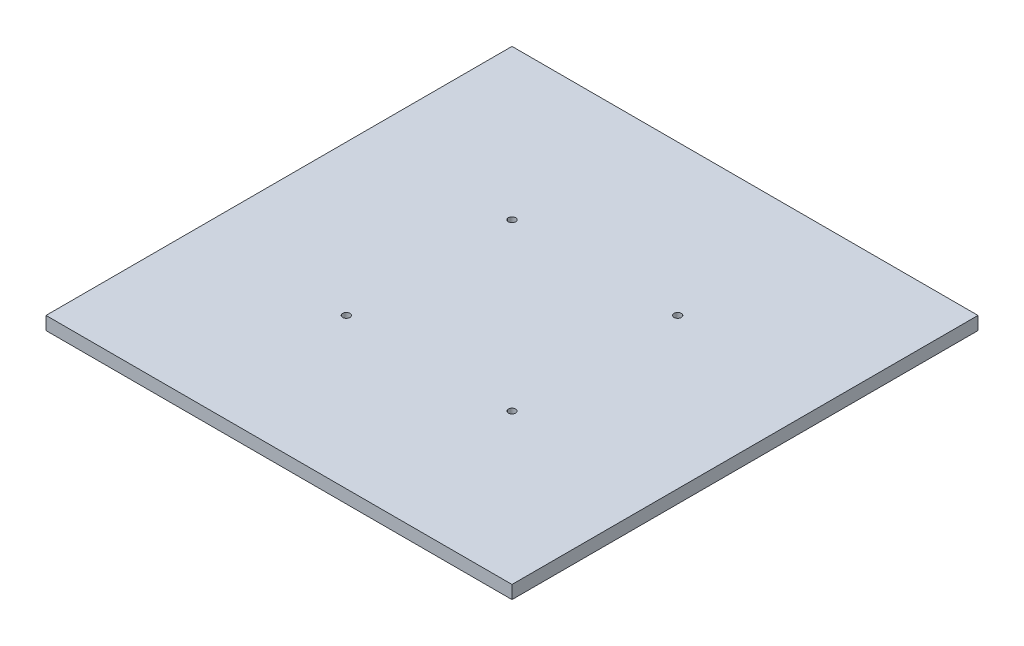
SolidWorks part; units mm, degrees
ref_plane "Front Plane" through (0, 0, 0) normal (0, 0, 1) x (1, 0, 0)
ref_plane "Top Plane" through (0, 0, 0) normal (0, 1, 0) x (1, 0, 0)
ref_plane "Right Plane" through (0, 0, 0) normal (1, 0, 0) x (0, 0, -1)
sketch "Esboço1" plane through (0, 0, 0) normal (0, 1, 0) x (1, 0, 0)
  line L1 (-225, -225) -> (225, -225)
  line L2 (-225, -225) -> (-225, 225)
  line L3 (-225, 225) -> (225, 225)
  line L4 (225, -225) -> (225, 225)
  line L5 (-225, -225) -> (225, 225) construction
  line L6 (-225, 225) -> (225, -225) construction
  point P0 (0, 0)
  dimension "D1" = 450
  dimension "D2" = 450
extrude "Ressalto-extrusão1" add sketch "Esboço1" along normal blind 12.7
sketch "Esboço2" plane through (0, 12.7, 0) normal (0, 1, 0) x (1, 0, 0)
  line L1 (-80, -80) -> (80, -80) construction
  line L2 (-80, -80) -> (-80, 80) construction
  line L3 (-80, 80) -> (80, 80) construction
  line L4 (80, -80) -> (80, 80) construction
  line L5 (-80, -80) -> (80, 80) construction
  line L6 (-80, 80) -> (80, -80) construction
  point P0 (0, 0)
  dimension "D1" = 160
  dimension "D2" = 160
hole_wizard "Furo roscado de M8x1.01" positions "Esboço3" profile "Esboço4" tap size "M8x1.0" standard "Ansi Metric" end condition through all
sketch "Esboço3" plane through (0, 12.7, 0) normal (0, 1, 0) x (1, 0, 0)
  point P0 (-80, 80)
  point P3 (80, 80)
  point P6 (80, -80)
  point P9 (-80, -80)
sketch "Esboço4" plane through (-80, 12.7, -80) normal (1, 0, 0) x (0, 0, 1)
  line L0 (0, 0) -> (0, 12.7)
  line L1 (0, 12.7) -> (3.5, 12.7)
  line L2 (3.5, 12.7) -> (3.5, 0)
  line L5 (3.5, 0) -> (0, 0)
  line L11 (0, -6.35) -> (0, 107.95) construction
  dimension "Thru Tap Drill Dia." = 7
  dimension "Thru Tap Drill Depth" = 12.7
cosmetic thread "Rosca de furo1" parameters "D2"=8
cosmetic thread "Rosca de furo2" parameters "D2"=8
cosmetic thread "Rosca de furo3" parameters "D2"=8
cosmetic thread "Rosca de furo4" parameters "D2"=8
